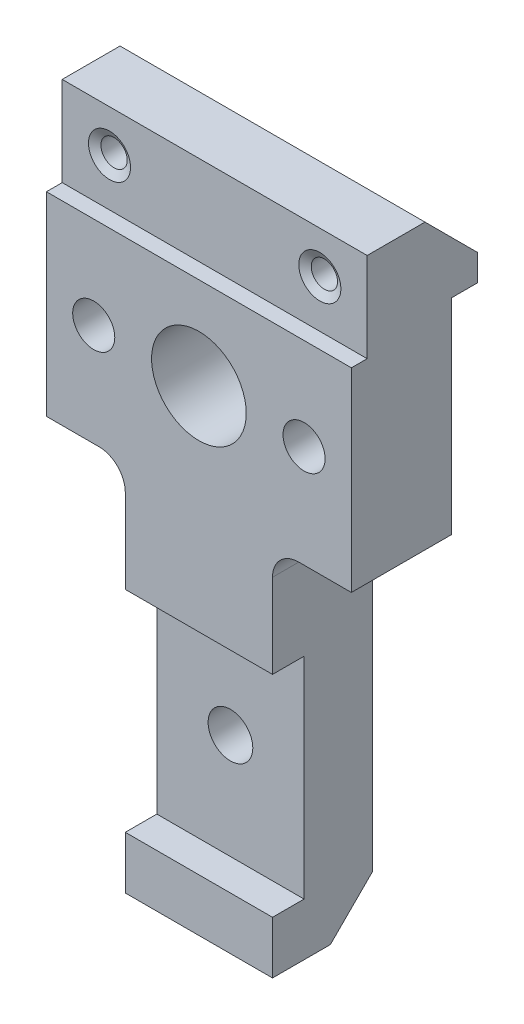
SolidWorks part; units mm, degrees
material "1.0503 (C45)"
ref_plane "Front Plane" through (0, 0, 0) normal (0, 0, 1) x (1, 0, 0)
ref_plane "Top Plane" through (0, 0, 0) normal (0, 1, 0) x (1, 0, 0)
ref_plane "Right Plane" through (0, 0, 0) normal (1, 0, 0) x (0, 0, -1)
sketch "Esquisse1" plane through (0, 0, 0) normal (1, 0, 0) x (0, 0, -1)
  line L0 (0, 0) -> (0, 10)
  line L1 (0, 10) -> (6, 10)
  line L2 (6, 10) -> (6, 50)
  line L3 (6, 50) -> (0, 50)
  line L4 (0, 50) -> (0, 108)
  line L5 (0, 108) -> (3, 108)
  line L6 (3, 108) -> (3, 125)
  line L7 (3, 125) -> (14, 125)
  line L8 (24, 115) -> (24, 110)
  line L9 (24, 110) -> (19, 110)
  line L10 (19, 110) -> (19, 8)
  line L11 (11, 0) -> (0, 0)
  line L12 (19, 8) -> (11, 0)
  line L13 (14, 125) -> (24, 115)
  point P9 (24, 125)
  point P12 (19, 0)
  dimension "D1" = 10
  dimension "D2" = 6
  dimension "D3" = 40
  dimension "D4" = 6
  dimension "D5" = 58
  dimension "D6" = 3
  dimension "D7" = 17
  dimension "D8" = 21
  dimension "D9" = 5
  dimension "D10" = 19
  dimension "D11" = 125
  dimension "D12" = 110
extrude "Boss.-Extru.1" add sketch "Esquisse1" along normal blind 58
sketch "Esquisse2" plane through (0, 0, 0) normal (0, 0, 1) x (1, 0, 0)
  line L0 (29, 108) -> (29, 78.6008) construction
  line L1 (58, 0) -> (43, 0)
  line L2 (58, 0) -> (58, 71)
  line L3 (58, 71) -> (48, 71)
  line L4 (43, 0) -> (43, 66)
  line L5 (58, 108) -> (0, 108) construction
  line L6 (58, 108) -> (58, 50) construction
  line L7 (58, 125) -> (0, 125) construction
  line L8 (15, 0) -> (15, 66)
  line L9 (0, 71) -> (10, 71)
  line L10 (0, 0) -> (0, 71)
  line L11 (0, 0) -> (15, 0)
  arc A0 (48, 71) -> (43, 66) centre (48, 66) ccw
  circle A1 centre (49, 90.5) radius 4
  arc A2 (10, 71) -> (15, 66) centre (10, 66) cw
  circle A3 centre (9, 90.5) radius 4
  circle A4 centre (29, 90.5) radius 9
  dimension "D3" = 5
  dimension "D4" = 8
  dimension "D5" = 9
  dimension "D7" = 18
  dimension "D1" = 71
  dimension "D2" = 15
  dimension "D6" = 34.5
  dimension "D8" = 34.5
extrude "Enlèv. mat.-Extru.1" cut sketch "Esquisse2" against normal through all
sketch "Esquisse3" plane through (0, 0, -19) normal (0, 0, -1) x (-1, 0, 0)
  circle A0 centre (-29, 90.5) radius 11
  circle A1 centre (-29, 90.5) radius 9 construction
  dimension "D1" = 22
extrude "Enlèv. mat.-Extru.2" cut sketch "Esquisse3" against normal blind 3.5
hole_wizard "Trou taraudé M61" positions "Esquisse4" profile "Esquisse5" tap size "M6" standard "ISO"
sketch "Esquisse4" plane through (0, 0, -3) normal (0, 0, 1) x (1, 0, 0)
  line L0 (58, 125) -> (0, 125) construction
  line L1 (58, 125) -> (58, 108) construction
  point P0 (49, 117)
  dimension "D1" = 8
  dimension "D2" = 9
sketch "Esquisse5" plane through (49, 117, -3) normal (1, 0, 0) x (0, -1, 0)
  line L0 (0, 0) -> (0, 16.5022)
  line L1 (0, 16.5022) -> (2.5, 15)
  line L2 (2.5, 15) -> (2.5, 0.866)
  line L3 (2.5, 0.866) -> (4, 0)
  line L5 (4, 0) -> (0, 0)
  line L6 (-2.5, 0.866) -> (-4, 0) construction
  line L10 (0, 16.5022) -> (-2.5, 15) construction
  line L11 (0, -6.35) -> (0, 107.95) construction
  dimension "Diamètre du trou pour taraudage" = 5
  dimension "Profondeur du trou pour taraudage" = 15
  dimension "Diamètre du fraisage entrant" = 8
  dimension "Angle du fraisage entrant" = 120
  dimension "Angle de pointe" = 118
cosmetic thread "Filetage de perçage1" parameters "D1"=12, "D2"=6
pattern_linear "Répétition linéaire1" count 2 spacing 40 along (-1, 0, 0) of "Trou taraudé M61"
hole_wizard "Trou taraudé M101" positions "Esquisse6" profile "Esquisse7" tap size "M10" standard "ISO" end condition through all
sketch "Esquisse6" plane through (0, 0, -6) normal (0, 0, 1) x (1, 0, 0)
  line L0 (43, 50) -> (15, 50) construction
  line L1 (43, 10) -> (43, 50) construction
  point P0 (29, 30)
  dimension "D1" = 20
  dimension "D2" = 14
sketch "Esquisse7" plane through (29, 30, -6) normal (1, 0, 0) x (0, -1, 0)
  line L0 (0, 0) -> (0, 18)
  line L1 (0, 18) -> (4.25, 18)
  line L2 (4.25, 18) -> (4.25, 0)
  line L5 (4.25, 0) -> (0, 0)
  line L11 (0, -6.35) -> (0, 107.95) construction
  dimension "Diamètre du trou pour taraudage jusqu'au prochain" = 8.5
  dimension "Profondeur du trou pour taraudage jusqu'au prochain" = 18
cosmetic thread "Filetage de perçage2" parameters "D2"=10
